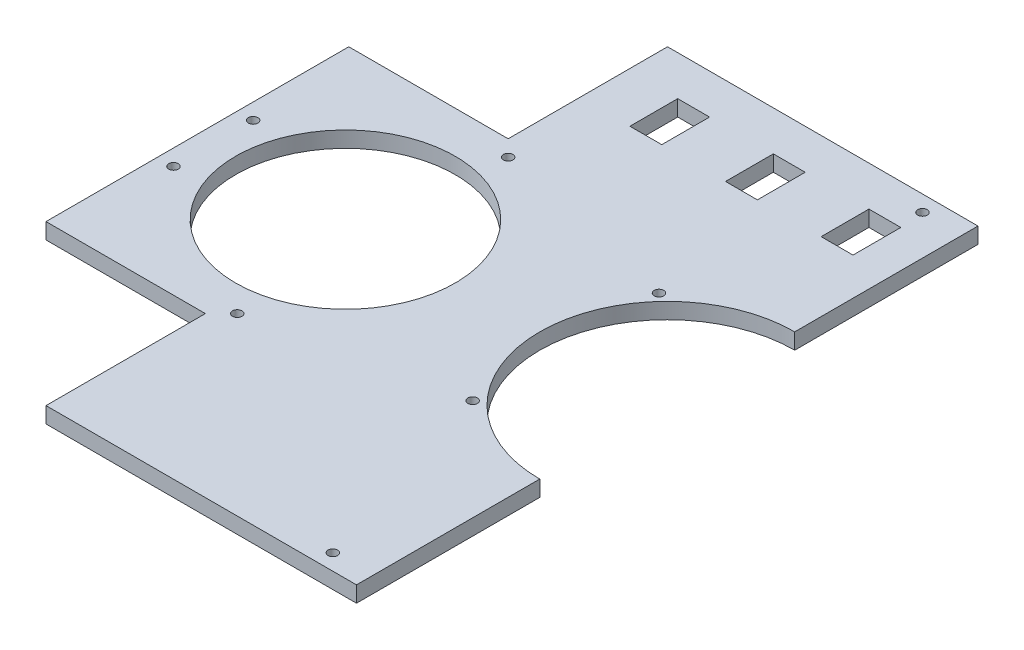
SolidWorks part; units mm, degrees
ref_plane "Plan de face" through (0, 0, 0) normal (0, 0, 1) x (1, 0, 0)
ref_plane "Plan de dessus" through (0, 0, 0) normal (0, 1, 0) x (1, 0, 0)
ref_plane "Plan de droite" through (0, 0, 0) normal (1, 0, 0) x (0, 0, -1)
sketch "Esquisse1" plane through (0, 0, 0) normal (0, 1, 0) x (1, 0, 0)
  line L1 (0, -97.5045) -> (-97.415, -97.5045)
  line L4 (-147.415, -47.5045) -> (-147.415, 47.4955)
  line L14 (-147.415, -47.5045) -> (-97.415, -47.5045)
  line L15 (-97.415, -47.5045) -> (-97.415, -97.5045)
  line L16 (-92.415, -92.5045) -> (-5, -92.5045) construction
  line L17 (-147.415, -42.5045) -> (-92.415, -42.5045) construction
  line L18 (-92.415, -42.5045) -> (-92.415, -97.5045) construction
  line L19 (0, 2.585) -> (-31.8198, -29.2348) construction
  line L20 (-147.415, -0.0045) -> (0, -0.0045) construction
  line L21 (0, -97.5045) -> (0, 2.585)
  line L27 (-142.415, 22.4955) -> (-142.415, -47.5045) construction
  line L29 (-142.415, -22.5045) -> (-142.415, 47.4955) construction
  line L34 (0, -2.5939) -> (-31.8198, 29.2259) construction
  line L35 (-92.415, 42.4955) -> (-92.415, 97.4955) construction
  line L36 (-147.415, 42.4955) -> (-92.415, 42.4955) construction
  line L37 (-92.415, 92.4955) -> (-5, 92.4955) construction
  line L38 (0, 97.4955) -> (0, -2.5939)
  line L39 (-97.415, 47.4955) -> (-97.415, 97.4955)
  line L40 (-147.415, 47.4955) -> (-97.415, 47.4955)
  line L42 (-97.415, 97.4955) -> (0, 97.4955)
  line L43 (-39.9161, 2.585) -> (0, 2.585) construction
  line L46 (-5, 97.585) -> (-5, -92.5045) construction
  circle A3 centre (-142.415, -42.5045) radius 1.5 construction
  circle A4 centre (-92.415, -42.5045) radius 1.5
  circle A5 centre (-92.415, -92.5045) radius 1.5 construction
  circle A14 centre (-142.415, -12.5045) radius 1.5
  circle A15 centre (-12.415, -92.5045) radius 1.5
  circle A16 centre (-92.415, 92.4955) radius 1.5 construction
  circle A18 centre (-31.8198, -29.2348) radius 1.5
  arc A34 (0, 39.9955) -> (0, -40.0045) centre (0, -0.0045) ccw
  circle A35 centre (-142.415, 42.4955) radius 1.5 construction
  circle A37 centre (-31.8198, 29.2259) radius 1.5
  circle A38 centre (-12.415, 92.4955) radius 1.5
  circle A39 centre (-142.415, 12.4955) radius 1.5
  circle A40 centre (-92.415, 42.4955) radius 1.5
  circle A45 centre (-100.9732, -0.0045) radius 34.4619
  point P0 (0, 0)
  point P56 (0, -0.0089)
  dimension "D7" = 30
  dimension "D2" = 3
  dimension "D12" = 95
  dimension "D14" = 5
  dimension "D15" = 40
  dimension "D3" = 45
  dimension "D4" = 5
  dimension "D5" = 5
  dimension "D6" = 5
  dimension "D8" = 80
  dimension "D9" = 5
  dimension "D10" = 50
  dimension "D11" = 97.415
  dimension "D13" = 45
extrude "Boss.-Extru.1" add sketch "Esquisse1" along normal blind 5
sketch "Esquisse2" plane through (0, 5, 0) normal (0, 1, 0) x (1, 0, 0)
  line L0 (-97.415, 77.4955) -> (0, 77.4955) construction
  line L1 (-81.7151, 84.9955) -> (-71.7151, 84.9955)
  line L2 (-81.7151, 84.9955) -> (-81.7151, 69.9955)
  line L3 (-81.7151, 69.9955) -> (-71.7151, 69.9955)
  line L4 (-71.7151, 84.9955) -> (-71.7151, 69.9955)
  line L5 (-81.7151, 84.9955) -> (-71.7151, 69.9955) construction
  line L6 (-81.7151, 69.9955) -> (-71.7151, 84.9955) construction
  line L11 (-51.7151, 84.9955) -> (-51.7151, 69.9955)
  line L12 (-51.7151, 84.9955) -> (-41.7151, 84.9955)
  line L17 (-41.7151, 84.9955) -> (-41.7151, 69.9955)
  line L18 (-51.7151, 69.9955) -> (-41.7151, 69.9955)
  line L19 (-97.415, 47.4955) -> (-97.415, 97.4955) construction
  line L20 (0, 97.4955) -> (0, 39.9955) construction
  line L21 (-97.415, 97.4955) -> (0, 97.4955) construction
  line L22 (-21.7151, 84.9955) -> (-21.7151, 69.9955)
  line L23 (-21.7151, 84.9955) -> (-11.7151, 84.9955)
  line L24 (-11.7151, 84.9955) -> (-11.7151, 69.9955)
  line L25 (-21.7151, 69.9955) -> (-11.7151, 69.9955)
  point P0 (-76.7151, 77.4955)
  dimension "D1" = 20
  dimension "D2" = 10
  dimension "D3" = 15
  dimension "D4" = 3
extrude "Enlèv. mat.-Extru.1" cut sketch "Esquisse2" against normal up to next
